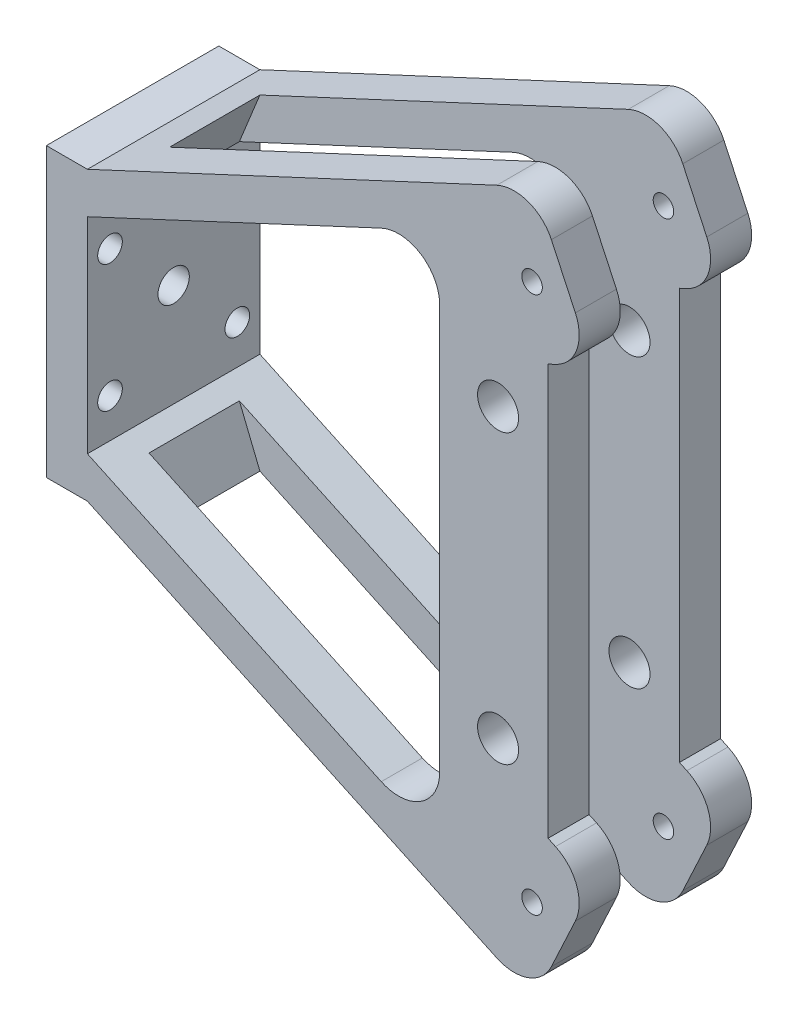
SolidWorks part; units mm, degrees
ref_plane "前视基准面" through (0, 0, 0) normal (0, 0, 1) x (1, 0, 0)
ref_plane "上视基准面" through (0, 0, 0) normal (0, 1, 0) x (1, 0, 0)
ref_plane "右视基准面" through (0, 0, 0) normal (1, 0, 0) x (0, 0, -1)
sketch "草图1" plane through (-10, 0, 0) normal (1, 0, 0) x (0, 0, -1)
  line L6 (-21, -35) -> (21, -35)
  line L7 (-21, -35) -> (-21, 35)
  line L8 (-21, 35) -> (21, 35)
  line L9 (21, -35) -> (21, 35)
  line L10 (-35.5389, 0) -> (34.4488, 0) construction
  line L11 (0, 0) -> (0, -48.1521) construction
  circle A0 centre (0, 0) radius 3.8156
  dimension "D1" = 70
  dimension "D2" = 42
  dimension "D3" = 35
  dimension "D4" = 21
extrude "凸台-拉伸1" add sketch "草图1" along normal blind 10
sketch "草图2" plane through (0, 0, 21) normal (0, 0, 1) x (1, 0, 0)
  line L4 (0, 25) -> (100, 25) construction
  line L12 (0, 35) -> (99.6939, 81.488)
  line L13 (112.9831, 76.6511) -> (118.8197, 64.1345)
  line L14 (113.9828, 50.8452) -> (112.1702, 50)
  line L15 (112.1702, 50) -> (112.1702, 0)
  line L16 (-96.7396, 0) -> (136.8957, 0) construction
  line L17 (112.1702, 0) -> (85.7803, 0)
  line L18 (85.7803, 0) -> (85.7803, 49.3031)
  line L19 (71.5541, 58.3662) -> (0, 25)
  line L20 (0, 25) -> (0, 35)
  circle A3 centre (100, 35) radius 5
  circle A4 centre (108.2772, 65.4293) radius 2.5
  arc A5 (113.9828, 50.8452) -> (118.8197, 64.1345) centre (109.7566, 59.9083) ccw
  arc A6 (112.9831, 76.6511) -> (99.6939, 81.488) centre (103.92, 72.4249) ccw
  arc A7 (85.7803, 49.3031) -> (71.5541, 58.3662) centre (75.7803, 49.3031) ccw
  point P14 (123.0459, 55.0714)
  point P17 (108.7569, 85.7142)
  point P20 (85.7803, 65)
  dimension "D6" = 10
  dimension "D1" = 25
  dimension "D2" = 120
  dimension "D3" = 12
  dimension "D4" = 50
  dimension "D5" = 65
extrude "凸台-拉伸2" add sketch "草图2" against normal blind 10 separate body
mirror "镜向5" about plane through (0, 0, 0) normal (0, 1, 0) of "凸台-拉伸2"
mirror "镜向23" about plane through (0, 0, 0) normal (0, 0, 1) of "镜向5", "凸台-拉伸1", "凸台-拉伸2"
sketch "草图3" plane through (0, 0, 0) normal (1, 0, 0) x (0, 0, -1)
  line L0 (-15.5, 15.5) -> (15.5, 15.5) construction
  line L1 (15.5, 15.5) -> (15.5, -15.5) construction
  line L2 (15.5, -15.5) -> (-15.5, -15.5) construction
  line L3 (-15.5, -15.5) -> (-15.5, 15.5) construction
  line L4 (0, 0) -> (0, 40.9649) construction
  line L5 (-35.5389, 0) -> (34.4488, 0) construction
  circle A0 centre (15.5, 15.5) radius 3
  circle A1 centre (15.5, -15.5) radius 3
  circle A2 centre (-15.5, -15.5) radius 3
  circle A3 centre (-15.5, 15.5) radius 3
  dimension "D5" = 6
  dimension "D1" = 31
  dimension "D2" = 31
  dimension "D3" = 15.5
  dimension "D4" = 15.5
extrude "切除-拉伸1" cut sketch "草图3" against normal blind 5
sketch "草图4" plane through (-5, 0, 0) normal (1, 0, 0) x (0, 0, -1)
  line L0 (-15.5, 15.5) -> (15.5, 15.5) construction
  line L1 (15.5, 15.5) -> (15.5, -15.5) construction
  line L2 (15.5, -15.5) -> (-15.5, -15.5) construction
  line L3 (-15.5, -15.5) -> (-15.5, 15.5) construction
  circle A0 centre (15.5, 15.5) radius 1.5
  circle A1 centre (-15.5, 15.5) radius 1.5
  circle A2 centre (-15.5, -15.5) radius 1.5
  circle A3 centre (15.5, -15.5) radius 1.5
  dimension "D1" = 3
extrude "切除-拉伸2" cut sketch "草图4" against normal through all
sketch "草图5" plane through (0, 0, 0) normal (0, 0, 1) x (1, 0, 0)
  line L0 (0, 35) -> (0, 25) construction
  line L1 (0, 25) -> (71.5541, 58.3662) construction
  line L2 (99.6939, 81.488) -> (0, 35) construction
  line L3 (0, 35) -> (0, 25)
  line L4 (0, 25) -> (5, 27.3315)
  line L5 (10, 39.6631) -> (0, 35)
  line L7 (10, 39.6631) -> (5, 27.3315)
extrude "凸台-拉伸3" add sketch "草图5" along normal mid plane 22
mirror "镜向24" about plane through (0, 0, 0) normal (0, 1, 0) of "凸台-拉伸3"
